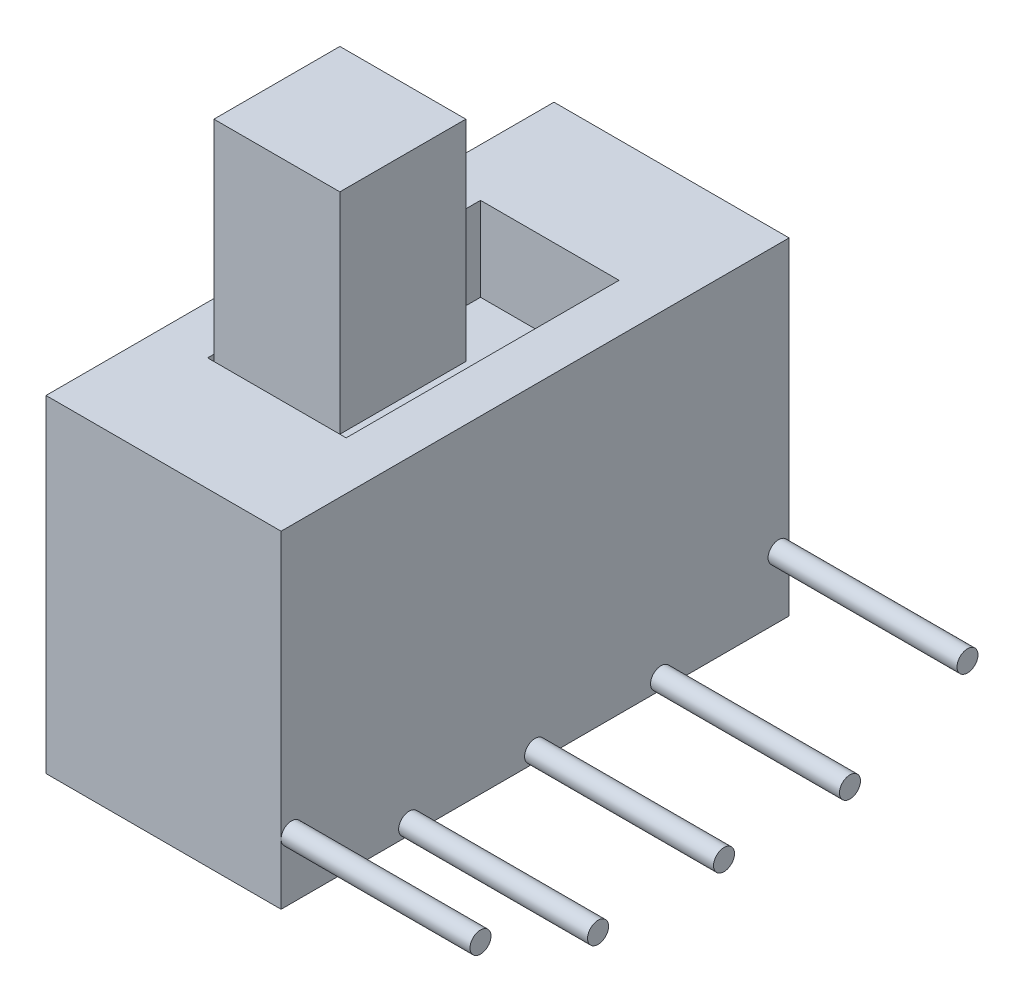
SolidWorks part; units mm, degrees
ref_plane "前视" through (0, 0, 0) normal (0, 0, 1) x (1, 0, 0)
ref_plane "上视" through (0, 0, 0) normal (0, 1, 0) x (1, 0, 0)
ref_plane "右视" through (0, 0, 0) normal (1, 0, 0) x (0, 0, -1)
sketch "草图1" plane through (0, 0, 0) normal (0, 1, 0) x (1, 0, 0)
  line L0 (0, 84.5395) -> (0, -95.7315) construction
  line L1 (-112.9192, 0) -> (128.508, 0) construction
  line L3 (-2.8, 6.05) -> (2.8, 6.05)
  line L4 (-2.8, 6.05) -> (-2.8, -6.05)
  line L5 (-2.8, -6.05) -> (2.8, -6.05)
  line L6 (2.8, 6.05) -> (2.8, -6.05)
  dimension "D1" = 5.6
  dimension "D2" = 12.1
extrude "拉伸1" add sketch "草图1" along normal blind 7.8
sketch "草图2" plane through (0, 7.8, 0) normal (0, 1, 0) x (-1, 0, 0)
  line L0 (0, -9.1531) -> (0, 9.348) construction
  line L1 (-6.307, 0) -> (6.9767, 0) construction
  line L3 (-1.65, -3.35) -> (1.65, -3.35) construction
  line L4 (-1.65, -3.35) -> (-1.65, 3.35) construction
  line L5 (-1.65, 3.35) -> (1.65, 3.35) construction
  line L6 (1.65, -3.35) -> (1.65, 3.35) construction
  line L7 (-1.5, 0.35) -> (1.5, 0.35)
  line L8 (-1.5, 0.35) -> (-1.5, 3.35)
  line L9 (-1.5, 3.35) -> (1.5, 3.35)
  line L10 (1.5, 0.35) -> (1.5, 3.35)
  dimension "D1" = 6.7
  dimension "D2" = 3.3
  dimension "D3" = 3
  dimension "D4" = 3
extrude "拉伸2" add sketch "草图2" along normal blind 5
sketch "草图3" plane through (2.8, 0, 0) normal (1, 0, 0) x (0, 0, -1)
  line L0 (0, 0) -> (0, 10.9566) construction
  line L1 (-6.05, 0) -> (6.05, 0) construction
  circle A0 centre (-3, 0.25) radius 0.25
  circle A1 centre (0, 0.25) radius 0.25
  circle A2 centre (3, 0.25) radius 0.25
  circle A3 centre (5.8, 1.45) radius 0.25
  circle A4 centre (-5.8, 1.45) radius 0.25
  dimension "D1" = 0.5
  dimension "D2" = 0.5
  dimension "D3" = 0.5
  dimension "D5" = 0.5
  dimension "D4" = 3
  dimension "D6" = 11.6
  dimension "D7" = 1.2
extrude "拉伸3" add sketch "草图3" along normal blind 4.5
sketch "草图4" plane through (-2.8, 0, 0) normal (-1, 0, 0) x (0, 0, 1)
  line L0 (0, -5.0374) -> (0, 17.1437) construction
sketch "草图5" plane through (0, 7.8, 0) normal (0, 1, 0) x (-1, 0, 0)
  line L0 (0, -8.8679) -> (0, 9.7834) construction
  line L1 (-1.65, -3.15) -> (1.65, -3.15)
  line L2 (-1.65, -3.15) -> (-1.65, 3.35)
  line L3 (-1.65, 3.35) -> (1.65, 3.35)
  line L4 (1.65, -3.15) -> (1.65, 3.35)
  line L5 (1.5, 3.35) -> (-1.5, 3.35) construction
  dimension "D1" = 3.3
  dimension "D2" = 6.5
extrude "切除-拉伸1" cut sketch "草图5" against normal blind 2
sketch "草图6" plane through (-2.8, 0, 0) normal (-1, 0, 0) x (0, 0, 1)
  line L0 (0, 0) -> (0, 19.3638)
